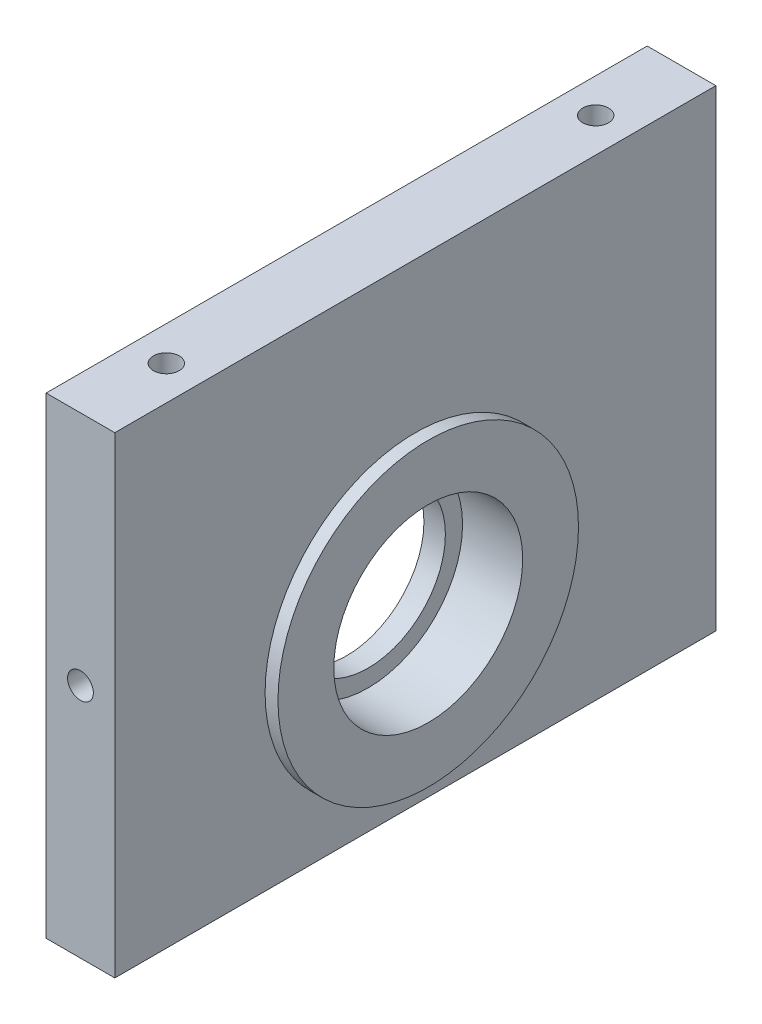
SolidWorks part; units mm, degrees
material "PE haute densité"
ref_plane "Plan de face" through (0, 0, 0) normal (0, 0, 1) x (1, 0, 0)
ref_plane "Plan de dessus" through (0, 0, 0) normal (0, 1, 0) x (1, 0, 0)
ref_plane "Plan de droite" through (0, 0, 0) normal (1, 0, 0) x (0, 0, -1)
sketch "Esquisse1" plane through (0, 0, 0) normal (1, 0, 0) x (0, 0, -1)
  line L1 (-35, -20) -> (35, -20)
  line L2 (-35, -20) -> (-35, 35)
  line L3 (-35, 35) -> (35, 35)
  line L4 (35, -20) -> (35, 35)
  line L5 (-35, -20) -> (35, 35) construction
  line L6 (-35, 35) -> (35, -20) construction
  circle A0 centre (0, 0) radius 9
  point P0 (0, 7.5)
  dimension "D1" = 18
  dimension "D4" = 20
  dimension "D2" = 70
  dimension "D3" = 55
extrude "Boss.-Extru.1" add sketch "Esquisse1" along normal mid plane 8
sketch "Esquisse2" plane through (4, 0, 0) normal (1, 0, 0) x (0, 0, -1)
  circle A0 centre (0, 0) radius 11
  dimension "D1" = 22
extrude "Enlèv. mat.-Extru.1" cut sketch "Esquisse2" against normal blind 5.5
hole_wizard "Trou taraudé M4x0.71" positions "Esquisse4" profile "Esquisse3" tap size "M4x0.7" standard "Ansi Metric"
sketch "Esquisse4" plane through (0, -20, 0) normal (0, -1, 0) x (-1, 0, 0)
  line L0 (0, -25) -> (0, 25) construction
  point P0 (0, -25)
  point P2 (0, 25)
  dimension "D1" = 50
sketch "Esquisse3" plane through (0, -20, 25) normal (1, 0, 0) x (0, 0, -1)
  line L0 (0, 0) -> (0, 15.9013)
  line L1 (0, 15.9013) -> (1.5, 15)
  line L2 (1.5, 15) -> (1.5, 0)
  line L5 (1.5, 0) -> (0, 0)
  line L10 (0, 15.9013) -> (-1.5, 15) construction
  line L11 (0, -6.35) -> (0, 107.95) construction
  dimension "Diamètre du trou pour taraudage" = 3
  dimension "Profondeur du trou pour taraudage" = 15
  dimension "Angle de pointe" = 118
cosmetic thread "Filetage de perçage1" parameters "D1"=10, "D2"=4
cosmetic thread "Filetage de perçage2" parameters "D1"=10, "D2"=4
hole_wizard "Trou taraudé M4x0.72" positions "Esquisse6" profile "Esquisse5" tap size "M4x0.7" standard "Ansi Metric"
sketch "Esquisse6" plane through (0, 35, 0) normal (0, 1, 0) x (1, 0, 0)
  line L0 (0, -25) -> (0, 25) construction
  point P0 (0, -25)
  point P2 (0, 25)
  dimension "D1" = 50
sketch "Esquisse5" plane through (0, 35, 25) normal (1, 0, 0) x (0, 0, 1)
  line L0 (0, 0) -> (0, 15.9013)
  line L1 (0, 15.9013) -> (1.5, 15)
  line L2 (1.5, 15) -> (1.5, 0)
  line L5 (1.5, 0) -> (0, 0)
  line L10 (0, 15.9013) -> (-1.5, 15) construction
  line L11 (0, -6.35) -> (0, 107.95) construction
  dimension "Diamètre du trou pour taraudage" = 3
  dimension "Profondeur du trou pour taraudage" = 15
  dimension "Angle de pointe" = 118
cosmetic thread "Filetage de perçage3" parameters "D1"=10, "D2"=4
cosmetic thread "Filetage de perçage4" parameters "D1"=10, "D2"=4
hole_wizard "Trou taraudé M4x0.73" positions "Esquisse8" profile "Esquisse7" tap size "M4x0.7" standard "Ansi Metric"
sketch "Esquisse8" plane through (0, 0, 35) normal (0, 0, 1) x (1, 0, 0)
  line L0 (-4, 7.5) -> (4, 7.5) construction
  line L1 (-4, 35) -> (-4, -20) construction
  line L2 (4, 35) -> (4, -20) construction
  point P17 (0, 7.5)
sketch "Esquisse7" plane through (0, 7.5, 35) normal (1, 0, 0) x (0, -1, 0)
  line L0 (0, 0) -> (0, 15.9013)
  line L1 (0, 15.9013) -> (1.5, 15)
  line L2 (1.5, 15) -> (1.5, 0)
  line L5 (1.5, 0) -> (0, 0)
  line L10 (0, 15.9013) -> (-1.5, 15) construction
  line L11 (0, -6.35) -> (0, 107.95) construction
  dimension "Diamètre du trou pour taraudage" = 3
  dimension "Profondeur du trou pour taraudage" = 15
  dimension "Angle de pointe" = 118
cosmetic thread "Filetage de perçage5" parameters "D1"=10, "D2"=4
hole_wizard "Trou taraudé M4x0.74" positions "Esquisse10" profile "Esquisse9" tap size "M4x0.7" standard "Ansi Metric"
sketch "Esquisse10" plane through (0, 0, -35) normal (0, 0, -1) x (-1, 0, 0)
  line L0 (4, 7.5) -> (-4, 7.5) construction
  line L1 (-4, -20) -> (-4, 35) construction
  line L3 (4, -20) -> (4, 35) construction
  point P3 (0, 7.5)
sketch "Esquisse9" plane through (0, 7.5, -35) normal (1, 0, 0) x (0, 1, 0)
  line L0 (0, 0) -> (0, 15.9013)
  line L1 (0, 15.9013) -> (1.5, 15)
  line L2 (1.5, 15) -> (1.5, 0)
  line L5 (1.5, 0) -> (0, 0)
  line L10 (0, 15.9013) -> (-1.5, 15) construction
  line L11 (0, -6.35) -> (0, 107.95) construction
  dimension "Diamètre du trou pour taraudage" = 3
  dimension "Profondeur du trou pour taraudage" = 15
  dimension "Angle de pointe" = 118
cosmetic thread "Filetage de perçage6" parameters "D1"=10, "D2"=4
sketch "Esquisse11" plane through (-1.5, 0, 0) normal (1, 0, 0) x (0, 0, -1)
  circle A0 centre (0, 0) radius 11
  circle A1 centre (0, 0) radius 17.5
  circle A2 centre (0, 0) radius 11 construction
  dimension "D1" = 35
extrude "Boss.-Extru.2" add sketch "Esquisse11" along normal blind 7
